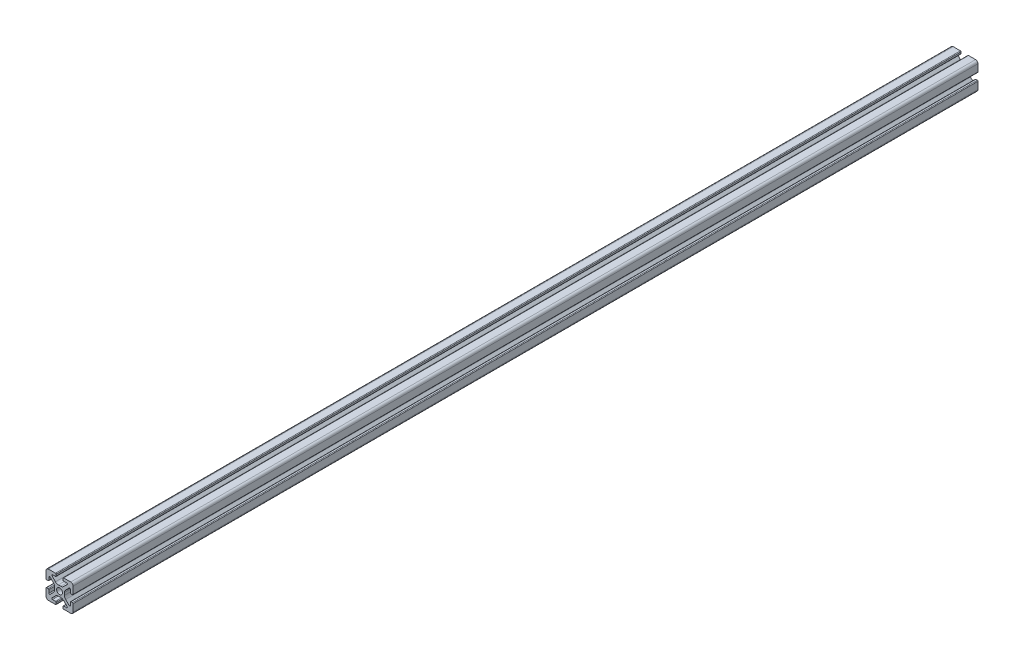
SolidWorks part; units mm, degrees
ref_plane "Front Plane" through (0, 0, 0) normal (0, 0, 1) x (1, 0, 0)
ref_plane "Top Plane" through (0, 0, 0) normal (0, 1, 0) x (1, 0, 0)
ref_plane "Right Plane" through (0, 0, 0) normal (1, 0, 0) x (0, 0, -1)
sketch "Sketch2" plane through (0, 0, 0) normal (0, 0, 1) x (1, 0, 0)
  line L0 (0, 10) -> (0, -10) construction
  line L1 (-10, 0) -> (10, 0) construction
  line L2 (2.5, -10) -> (10, -10)
  line L3 (10, -10) -> (10, -2.5)
  line L4 (2.5, -10) -> (2.5, -7.9246)
  line L5 (2.5, -7.9246) -> (6.4571, -7.9246)
  line L6 (6.4571, -7.9246) -> (2.1325, -3.6)
  line L7 (0, 0) -> (10, -10) construction
  line L8 (10, -2.5) -> (7.9246, -2.5)
  line L9 (7.9246, -2.5) -> (7.9246, -6.4571)
  line L10 (7.9246, -6.4571) -> (3.6, -2.1325)
  line L11 (5.7623, -4.2948) -> (4.2948, -5.7623) construction
  circle A0 centre (0, 0) radius 2.15
  arc A1 (5.25, -7.9246) -> (5.6036, -7.0711) centre (5.25, -7.4246) ccw construction
  point P8 (0, -3.6)
  point P16 (5.0286, -5.0286)
  dimension "Center Hole Diameter" = 4.3
  dimension "D3" = 0.5
  dimension "Rail Height" = 20
  dimension "Rail Width" = 20
  dimension "T-Slot Width" = 5
  dimension "Slot Depth" = 6.4
  dimension "Slot Inner Width" = 11.5
sketch "Sketch3" plane through (0, 0, 0) normal (1, 0, 0) x (0, 0, -1)
  line L0 (-457.2, -10) -> (457.2, -10) construction
  line L1 (-431.8, 0) -> (431.8, 0) construction
  line L2 (0, 10) -> (0, -10) construction
  line L3 (0, 10) -> (0, -10) construction
  point P6 (-431.8, 0)
  point P8 (431.8, 0)
  dimension "Length" = 914.4
  dimension "D1" = 25.4
sketch "Sketch4" plane through (0, 0, 0) normal (0, 0, 1) x (1, 0, 0)
  line L0 (3, -10) -> (8.25, -10)
  line L1 (2.5, -10) -> (10, -10) construction
  line L2 (2.5, -10) -> (2.5, -7.9246) construction
  line L3 (2.5, -7.9246) -> (6.4571, -7.9246) construction
  line L4 (2.5, -8.4246) -> (2.5, -9.5)
  line L5 (3, -7.9246) -> (5.25, -7.9246)
  line L6 (0, -3.6) -> (0.8898, -3.6)
  line L7 (6.4571, -7.9246) -> (2.1325, -3.6) construction
  line L8 (3.0112, -4.4787) -> (5.6036, -7.0711)
  line L9 (10, -10) -> (10, -2.5) construction
  line L10 (7.9246, -6.4571) -> (3.6, -2.1325) construction
  line L11 (7.9246, -2.5) -> (7.9246, -6.4571) construction
  line L12 (7.9246, -5.25) -> (7.9246, -3)
  line L13 (10, -2.5) -> (7.9246, -2.5) construction
  line L14 (8.4246, -2.5) -> (9.5, -2.5)
  line L15 (10, -3) -> (10, -8.25)
  line L16 (7.0711, -5.6036) -> (4.4787, -3.0112)
  line L17 (3.6, 0) -> (3.6, -0.8898)
  line L18 (-10, 0) -> (10, 0) construction
  line L19 (0, -3.6) -> (0, -2.15)
  line L20 (0, 10) -> (0, -10) construction
  line L21 (3.6, 0) -> (2.15, 0)
  arc A0 (2.5, -9.5) -> (3, -10) centre (3, -9.5) ccw
  arc A1 (5.25, -7.9246) -> (5.6036, -7.0711) centre (5.25, -7.4246) ccw construction
  arc A2 (2.5, -8.4246) -> (3, -7.9246) centre (3, -8.4246) cw
  arc A3 (5.25, -7.9246) -> (5.6036, -7.0711) centre (5.25, -7.4246) ccw
  arc A4 (0.8898, -3.6) -> (3.0112, -4.4787) centre (0.8898, -6.6) cw
  arc A5 (8.25, -10) -> (10, -8.25) centre (8.25, -8.25) ccw
  arc A6 (7.0711, -5.6036) -> (7.9246, -5.25) centre (7.4246, -5.25) ccw
  arc A7 (7.9246, -3) -> (8.4246, -2.5) centre (8.4246, -3) cw
  arc A8 (9.5, -2.5) -> (10, -3) centre (9.5, -3) cw
  arc A9 (4.4787, -3.0112) -> (3.6, -0.8898) centre (6.6, -0.8898) cw
  circle A10 centre (0, 0) radius 2.15 construction
  arc A11 (0, -2.15) -> (2.15, 0) centre (0, 0) ccw
  dimension "D1" = 1.75
  dimension "D2" = 3
extrude "Boss-Extrude1" add sketch "Sketch4" along normal mid plane 500
mirror "Mirror1" about plane through (0, 0, 0) normal (1, 0, 0) of bodies 134
mirror "Mirror2" about plane through (0, 0, 0) normal (0, 1, 0) of bodies 135
scale "Scale1" bodies to scale 136 scale about centroid uniform scaling no x scale factor 0.75 y scale factor 0.75 z scale factor 1
equation "\"D3@Sketch2\"=\"T-Slot Width@Sketch2\"*0.1"
equation "\"D1@Sketch4\"=\"D3@Sketch2\"*3.5"
equation "\"D2@Sketch4\"=\"D3@Sketch2\"*6"
equation "\"D1@Boss-Extrude1\"=\"Length@Sketch3\""
